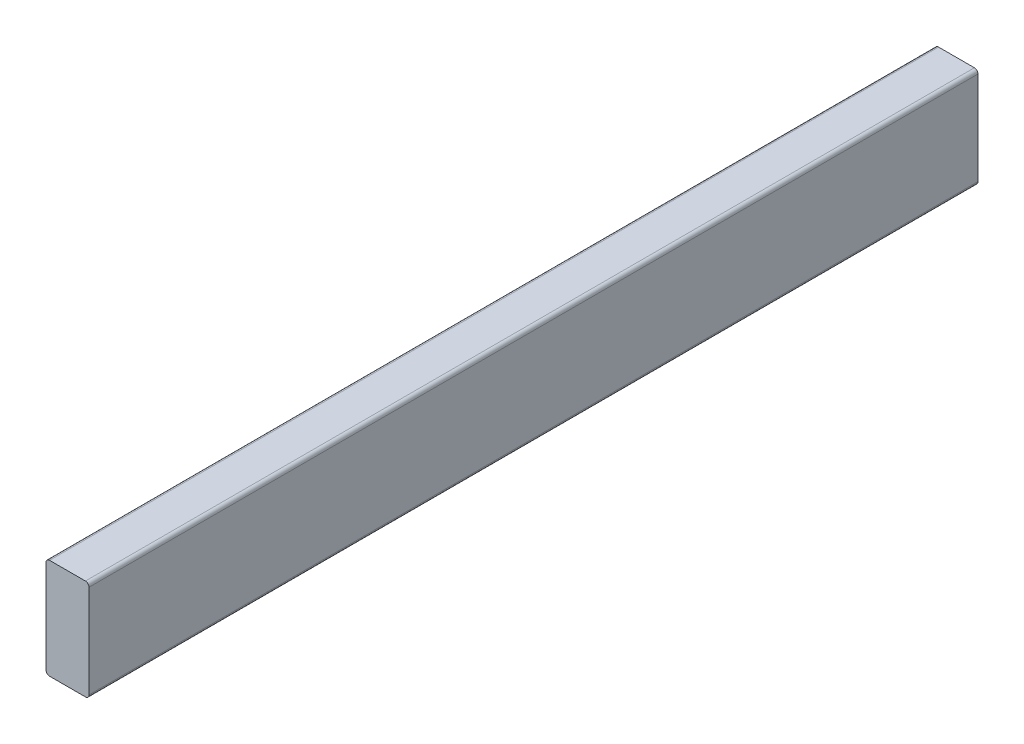
SolidWorks part; units mm, degrees
material "Pine"
ref_plane "Front Plane" through (0, 0, 0) normal (0, 0, 1) x (1, 0, 0)
ref_plane "Top Plane" through (0, 0, 0) normal (0, 1, 0) x (1, 0, 0)
ref_plane "Right Plane" through (0, 0, 0) normal (1, 0, 0) x (0, 0, -1)
sketch "Sketch1" plane through (0, 0, 0) normal (0, 0, 1) x (1, 0, 0)
  line L1 (0, 0) -> (38.1, 0)
  line L2 (0, 0) -> (0, 88.9)
  line L3 (0, 88.9) -> (38.1, 88.9)
  line L4 (38.1, 0) -> (38.1, 88.9)
  dimension "D1" = 38.1
  dimension "D2" = 88.9
extrude "Boss-Extrude1" add sketch "Sketch1" against normal mid plane 787.4
fillet "Fillet1" radius 3.175 4 edges at (0, 0, 0) (38.1, 0, 0) (0, 88.9, 0) (38.1, 88.9, 0)
